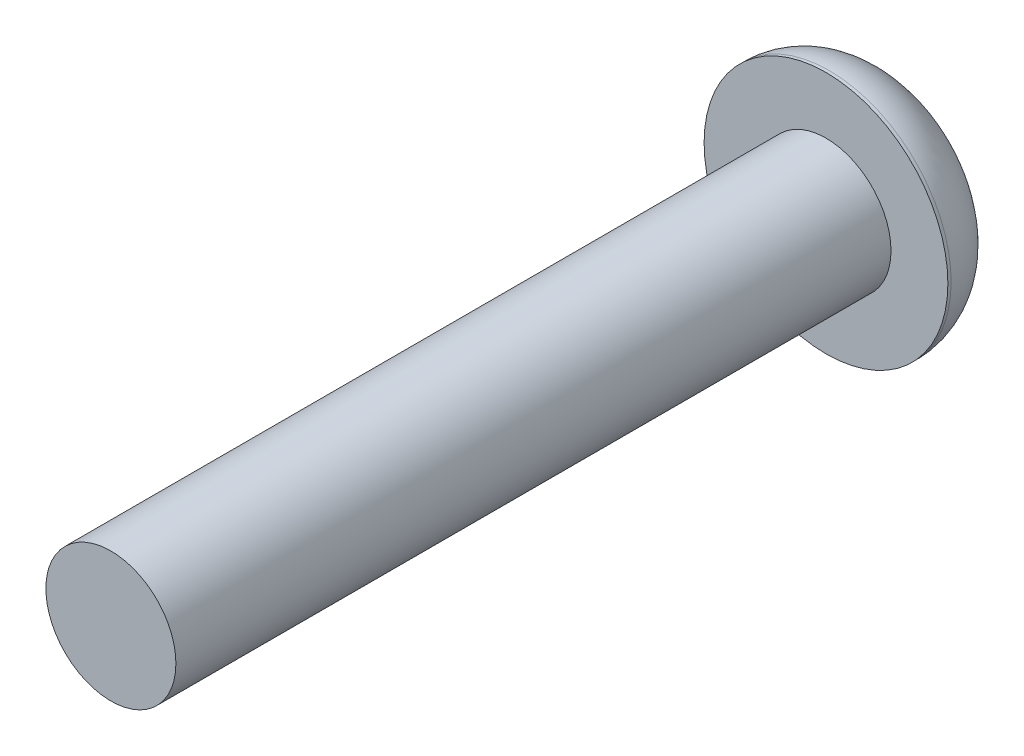
SolidWorks part; units mm, degrees
ref_plane "前视基准面" through (0, 0, 0) normal (0, 0, 1) x (1, 0, 0)
ref_plane "上视基准面" through (0, 0, 0) normal (0, 1, 0) x (1, 0, 0)
ref_plane "右视基准面" through (0, 0, 0) normal (1, 0, 0) x (0, 0, -1)
sketch "草图1" plane through (0, 0, 0) normal (0, 0, 1) x (1, 0, 0)
  circle A0 centre (0, 0) radius 2
extrude "凸台-拉伸1" add sketch "草图1" along normal blind 22
sketch "草图2" plane through (0, 0, 0) normal (0, 0, -1) x (-1, 0, 0)
  circle A0 centre (0, 0) radius 3.75
extrude "凸台-拉伸2" add sketch "草图2" along normal blind 2.1
fillet "圆角1" radius 2 1 edges at (-3.75, 0, -2.1)
